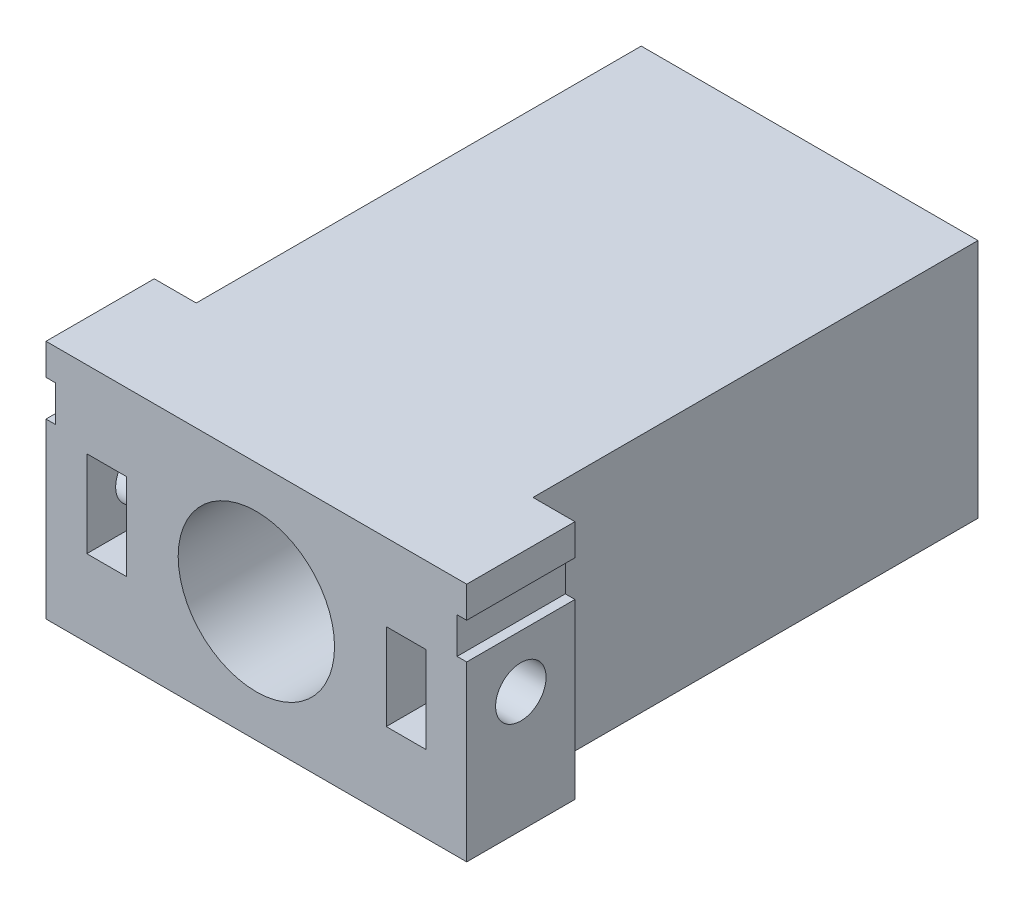
SolidWorks part; units mm, degrees
ref_plane "Płaszczyzna przednia" through (0, 0, 0) normal (0, 0, 1) x (1, 0, 0)
ref_plane "Płaszczyzna górna" through (0, 0, 0) normal (0, 1, 0) x (1, 0, 0)
ref_plane "Płaszczyzna prawa" through (0, 0, 0) normal (1, 0, 0) x (0, 0, -1)
sketch "Szkic1" plane through (0, 0, 0) normal (0, 0, 1) x (1, 0, 0)
  line L1 (14, -10) -> (-14, -10)
  line L2 (14, -10) -> (14, 10)
  line L3 (14, 10) -> (-14, 10)
  line L4 (-14, -10) -> (-14, 10)
  line L5 (14, -10) -> (-14, 10) construction
  line L6 (14, 10) -> (-14, -10) construction
  circle A0 centre (0, 0) radius 6.5
extrude "Dodanie-wyciągnięcie1" add sketch "Szkic1" along normal blind 46
sketch "Szkic2" plane through (0, 10, 0) normal (0, 1, 0) x (1, 0, 0)
  line L0 (14, -46) -> (14, -37)
  line L1 (14, -46) -> (14, 0) construction
  line L2 (14, -46) -> (14.1, -46)
  line L3 (14.1, -46) -> (14.1, -37)
  line L4 (14.1, -37) -> (14, -37)
  line L5 (0, -46) -> (0, -40.0528)
  line L6 (14, -46) -> (-14, -46) construction
  line L7 (-14, -46) -> (-14.1, -46)
  line L8 (-14.1, -46) -> (-14.1, -37)
  line L9 (-14, -46) -> (-14, -37)
  line L10 (-14.1, -37) -> (-14, -37)
  line M2 (-14, 0) -> (-14, -46)
  line M4 (14, -46) -> (14, 0)
extrude "Dodanie-wyciągnięcie2" add sketch "Szkic2" against normal up to surface (20 mm away) contours L10 L8 L7 M2 | L3 L4 L2 M4 up to face at (0, -10, 23)
sketch "Szkic3" plane through (14.1, 0, 0) normal (1, 0, 0) x (0, 0, -1)
  line L0 (-37, 0) -> (-41.5, 0)
  line L1 (-37, -10) -> (-37, 10) construction
  line L2 (-43.5785, 3.6) -> (-46, 3.6)
  line L3 (-37.3431, 0) -> (-39.4215, 3.6)
  line L4 (-39.4215, 3.6) -> (-43.5785, 3.6)
  line L5 (-43.5785, 3.6) -> (-45.6569, 0)
  line L6 (-45.6569, 0) -> (-43.5785, -3.6)
  line L7 (-43.5785, -3.6) -> (-39.4215, -3.6)
  line L8 (-39.4215, -3.6) -> (-37.3431, 0)
  line L9 (-46, -10) -> (-46, 10) construction
  line L10 (-43.5785, -3.6) -> (-46, -3.6)
  circle A0 centre (-41.5, 0) radius 3.6 construction
extrude "Wytnij-wyciągnięcie1" cut sketch "Szkic3" against normal blind 3.3
sketch "Szkic4" plane through (-14.1, 0, 0) normal (-1, 0, 0) x (0, 0, 1)
  line L0 (41.5, 10) -> (41.5, 0)
  line L1 (46, 10) -> (37, 10) construction
  line L2 (43.5785, 3.6) -> (46, 3.6)
  line L3 (45.6569, 0) -> (43.5785, 3.6)
  line L4 (43.5785, 3.6) -> (39.4215, 3.6)
  line L5 (39.4215, 3.6) -> (37.3431, 0)
  line L6 (37.3431, 0) -> (39.4215, -3.6)
  line L7 (39.4215, -3.6) -> (43.5785, -3.6)
  line L8 (43.5785, -3.6) -> (45.6569, 0)
  line L9 (46, -10) -> (46, 10) construction
  line L10 (43.5785, -3.6) -> (46, -3.6)
  circle A0 centre (41.5, 0) radius 3.6 construction
extrude "Wytnij-wyciągnięcie2" cut sketch "Szkic4" against normal blind 3.3
sketch "Szkic5" plane through (-14.1, 0, 0) normal (-1, 0, 0) x (0, 0, 1)
  line L0 (41.5, 10) -> (41.5, 0)
  line L1 (37, 10) -> (46, 10)
  line L2 (37, 10) -> (37, -10)
  line L3 (37, -10) -> (46, -10)
  line L4 (46, 10) -> (46, -10)
  circle A0 centre (41.5, 0) radius 2.1
extrude "Dodanie-wyciągnięcie3" add sketch "Szkic5" along normal blind 3.39
sketch "Szkic6" plane through (14.1, 0, 0) normal (1, 0, 0) x (0, 0, -1)
  line L0 (-46, 0) -> (-41.5, 0)
  line L1 (-46, 10) -> (-37, 10)
  line L2 (-46, 10) -> (-46, -10)
  line L3 (-46, -10) -> (-37, -10)
  line L4 (-37, 10) -> (-37, -10)
  circle A0 centre (-41.5, 0) radius 2.1
extrude "Dodanie-wyciągnięcie4" add sketch "Szkic6" along normal blind 3.39
sketch "Szkic7" plane through (-17.49, 0, 0) normal (-1, 0, 0) x (0, 0, 1)
  line L0 (37, 10) -> (37, 4.4)
  line L1 (37, -10) -> (37, 10) construction
  line L2 (37, 4.4) -> (46.4483, 4.4)
  line L3 (46.4483, 10) -> (46.4483, 7.4)
  line L4 (46, 10) -> (37, 10) construction
  line L5 (46.4483, 7.4) -> (37, 7.4)
  line L6 (46.4483, 7.4) -> (46.4483, 4.4)
extrude "Wytnij-wyciągnięcie3" cut sketch "Szkic7" against normal blind 0.8 contours L6 L5 L0 L2
sketch "Szkic8" plane through (17.49, 0, 0) normal (1, 0, 0) x (0, 0, -1)
  line L0 (-37, 7.4) -> (-37, 4.4)
  line L1 (-37, -10) -> (-37, 10) construction
  line L2 (-37, 4.4) -> (-46, 4.4)
  line L3 (-46, 10) -> (-46, -10) construction
  line L4 (-46, 10) -> (-46, 7.4)
  line L5 (-46, 7.4) -> (-37, 7.4)
  line L6 (-46, 4.4) -> (-46, 7.4)
  line M4 (-46, 10) -> (-46, -10)
  line M6 (-37, -10) -> (-37, 10)
extrude "Wytnij-wyciągnięcie4" cut sketch "Szkic8" against normal blind 0.8 contours L5 L2 M4 M6
